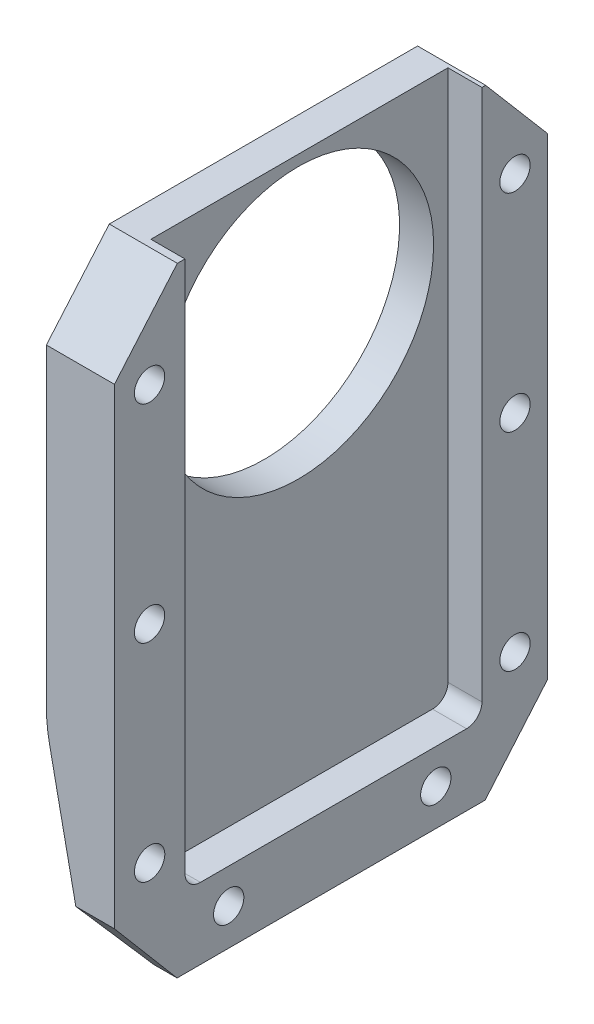
SolidWorks part; units mm, degrees
material "PET"
ref_plane "Front Plane" through (0, 0, 0) normal (0, 0, 1) x (1, 0, 0)
ref_plane "Top Plane" through (0, 0, 0) normal (0, 1, 0) x (1, 0, 0)
ref_plane "Right Plane" through (0, 0, 0) normal (1, 0, 0) x (0, 0, -1)
sketch "Sketch1" plane through (0, 0, 0) normal (0, 0, 1) x (1, 0, 0)
  line L0 (0, 0) -> (0, 50.8)
  line L1 (0, 50.8) -> (-5.588, 50.8)
  line L2 (-5.588, 50.8) -> (-5.588, 17.78)
  line L3 (-5.588, 17.78) -> (-1.9166, 0)
  line L4 (-1.9166, 0) -> (0, 0)
extrude "Boss-Extrude1" add sketch "Sketch1" along normal blind 35.56
fillet "Fillet1" radius 12.7 1 edges at (-5.588, 17.78, 17.78)
sketch "Sketch6" plane through (0, 0, 0) normal (1, 0, 0) x (0, 0, -1)
  line L0 (-17.78, 50.8) -> (-17.78, 0) construction
  line L1 (-35.56, 50.8) -> (0, 50.8) construction
  line L2 (-35.56, 0) -> (0, 0) construction
  line L4 (-29.772, 50.8) -> (-5.388, 50.8)
  line L5 (-29.772, 50.8) -> (-29.772, 5.842)
  line L6 (-29.772, 5.842) -> (-5.388, 5.842)
  line L7 (-5.388, 50.8) -> (-5.388, 5.842)
  dimension "D1" = 44.958
  dimension "D2" = 24.384
extrude "Cut-Extrude1" cut sketch "Sketch6" against normal blind 2.794
fillet "Fillet2" radius 1.27 2 edges at (-1.397, 5.842, 29.772) (-1.397, 5.842, 5.388)
sketch "Sketch10" plane through (0, 0, 0) normal (1, 0, 0) x (0, 0, -1)
  line L0 (-35.56, 44.7804) -> (-30.3976, 50.8)
  line L1 (-35.56, 0) -> (-35.56, 50.8) construction
  line L2 (-35.56, 50.8) -> (-29.772, 50.8) construction
  line L3 (-30.3976, 50.8) -> (-35.56, 50.8)
  line L4 (-35.56, 50.8) -> (-35.56, 44.7804)
extrude "Cut-Extrude3" cut sketch "Sketch10" against normal through all
sketch "Sketch11" plane through (0, 0, 0) normal (1, 0, 0) x (0, 0, -1)
  line L0 (-5.0855, 50.8) -> (0, 50.8)
  line L1 (-5.388, 50.8) -> (0, 50.8) construction
  line L2 (0, 50.8) -> (0, 44.8249)
  line L3 (0, 0) -> (0, 50.8) construction
  line L4 (0, 44.8249) -> (-5.0855, 50.8)
  line L5 (0, 6.0295) -> (-5.1287, 0)
  line L6 (-35.56, 0) -> (0, 0) construction
  line L7 (-5.1287, 0) -> (0, 0)
  line L8 (0, 0) -> (0, 6.0295)
  line L9 (-35.56, 6.0712) -> (-35.56, 0)
  line L10 (-35.56, 0) -> (-35.56, 44.7804) construction
  line L11 (-35.56, 0) -> (-30.4171, 0)
  line L12 (-30.4171, 0) -> (-35.56, 6.0712)
extrude "Cut-Extrude4" cut sketch "Sketch11" against normal through all
hole_wizard "7/8 (0.875) Diameter Hole1" positions "Sketch12" profile "Sketch13" hole size "7/8" standard "ANSI Inch" end condition through all
sketch "Sketch12" plane through (-5.588, 0, 0) normal (-1, 0, 0) x (0, 0, 1)
  point P0 (17.6785, 38.8095)
sketch "Sketch13" plane through (-5.588, 38.8095, 17.6785) normal (0, 1, 0) x (0, 0, 1)
  line L0 (0, 0) -> (0, 5.588)
  line L1 (0, 5.588) -> (11.1125, 5.588)
  line L2 (11.1125, 5.588) -> (11.1125, 0)
  line L5 (11.1125, 0) -> (0, 0)
  line L11 (0, -6.35) -> (0, 107.95) construction
  dimension "Thru Hole Dia." = 22.225
  dimension "Thru Hole Depth" = 5.588
hole_wizard "#40 (0.098) Diameter Hole1" positions "Sketch14" profile "Sketch15" hole size "#40" standard "ANSI Inch" end condition through all
sketch "Sketch14" plane through (-5.588, 0, 0) normal (-1, 0, 0) x (0, 0, 1)
  line L0 (2.6785, 43.3095) -> (32.6785, 43.3095) construction
  line L1 (32.6785, 43.3095) -> (32.6785, 26.3095) construction
  line L2 (32.6785, 26.3095) -> (2.6785, 26.3095) construction
  line L3 (2.6785, 26.3095) -> (2.6785, 9.3095) construction
  line L4 (2.6785, 9.3095) -> (32.6729, 9.3095) construction
  point P0 (2.6785, 43.3095)
  point P3 (2.6785, 26.3095)
  point P6 (2.6785, 9.3095)
  point P9 (9.1785, 3.0095)
  point P12 (26.1819, 2.9992)
  point P14 (32.6729, 9.3095)
  point P16 (32.6785, 26.3095)
  point P19 (32.6785, 43.3095)
  dimension "D1" = 17
  dimension "D2" = 17
  dimension "D3" = 30
sketch "Sketch15" plane through (-5.588, 43.3095, 2.6785) normal (0, 1, 0) x (0, 0, 1)
  line L0 (0, 0) -> (0, 5.588)
  line L1 (0, 5.588) -> (1.2446, 5.588)
  line L2 (1.2446, 5.588) -> (1.2446, 0.635)
  line L3 (1.2446, 0.635) -> (1.8796, 0)
  line L5 (1.8796, 0) -> (0, 0)
  line L6 (-1.2446, 0.635) -> (-1.8796, 0) construction
  line L11 (0, -6.35) -> (0, 107.95) construction
  dimension "Thru Hole Dia." = 2.4892
  dimension "Thru Hole Depth" = 5.588
  dimension "Near C'Sink Dia." = 3.7592
  dimension "Near C'Sink Angle" = 90
sketch "Sketch17" plane through (-5.588, 0, 0) normal (-1, 0, 0) x (0, 0, 1)
  line L0 (6.566, 38.8095) -> (28.791, 38.8095) construction
  circle A0 centre (17.6785, 38.8095) radius 11.1125 construction
  circle A1 centre (17.6785, 38.8095) radius 11.1125
  point P7 (17.6785, 38.8095)
